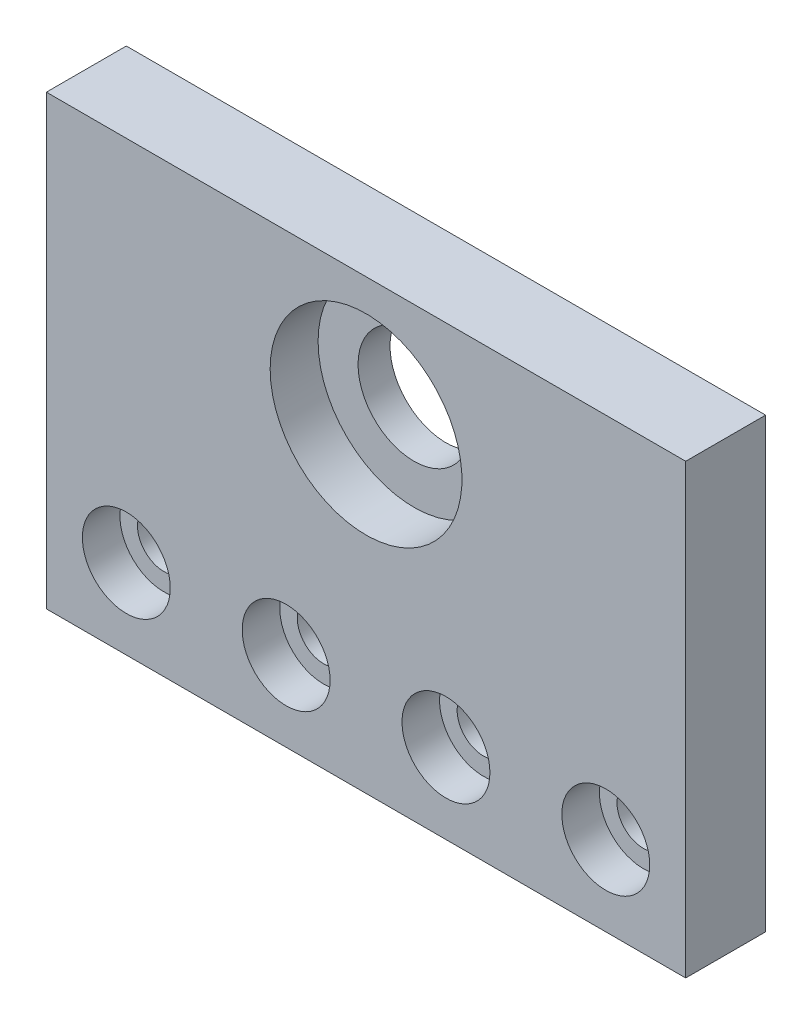
SolidWorks part; units mm, degrees
material "7A04-T6"
ref_plane "前视基准面" through (0, 0, 0) normal (0, 0, 1) x (1, 0, 0)
ref_plane "上视基准面" through (0, 0, 0) normal (0, 1, 0) x (1, 0, 0)
ref_plane "右视基准面" through (0, 0, 0) normal (1, 0, 0) x (0, 0, -1)
sketch "草图1" plane through (0, 0, 0) normal (0, 0, 1) x (1, 0, 0)
  line L1 (-40, -40) -> (40, -40)
  line L2 (-40, -40) -> (-40, 16)
  line L3 (-40, 16) -> (40, 16)
  line L4 (40, -40) -> (40, 16)
  point P4 (0, 16)
  dimension "D1" = 40
  dimension "D2" = 80
  dimension "D3" = 56
extrude "凸台-拉伸1" add sketch "草图1" against normal blind 10
sketch "草图2" plane through (0, 0, 0) normal (0, 0, 1) x (1, 0, 0)
  circle A0 centre (0, 0) radius 19
  dimension "D1" = 38
sketch "草图3" plane through (0, 0, 0) normal (0, 0, 1) x (1, 0, 0)
  line L0 (-40, -40) -> (40, -40) construction
  line L1 (40, -40) -> (40, 16) construction
  line L2 (0, 0) -> (0, -16.4447) construction
  point P0 (30, -30)
  point P9 (-30, -30)
  point P16 (10, -30)
  point P17 (-10, -30)
  point P18 (-30, -30)
  dimension "D1" = 10
  dimension "D2" = 10
  dimension "D3" = 4
hole_wizard "M6 内六角花型圆柱头螺钉的柱形沉头孔1" positions "草图3" profile "草图4" counterbore size "M6" standard "GB" end condition through all
sketch "草图4" plane through (30, -30, 0) normal (1, 0, 0) x (0, -1, 0)
  line L0 (0, 0) -> (0, 10)
  line L1 (0, 10) -> (3.3, 10)
  line L3 (3.3, 10) -> (3.3, 4.7)
  line L4 (3.3, 4.7) -> (5.5, 4.7)
  line L5 (5.5, 4.7) -> (5.5, 0)
  line L7 (5.5, 0) -> (0, 0)
  line L11 (0, -6.35) -> (0, 107.95) construction
  dimension "通孔孔直径" = 6.6
  dimension "通孔孔深度" = 10
  dimension "柱形沉头孔直径" = 11
  dimension "柱形沉头孔深度" = 4.7
sketch "草图5" plane through (0, 0, 0) normal (0, 0, 1) x (1, 0, 0)
  circle A0 centre (0, 0) radius 7
  dimension "D1" = 14
extrude "切除-拉伸1" cut sketch "草图5" against normal blind 10
sketch "草图6" plane through (0, 0, 0) normal (0, 0, -1) x (-1, 0, 0)
  circle A0 centre (0, 0) radius 12
  dimension "D1" = 24
extrude "切除-拉伸2" cut sketch "草图6" along normal blind 6
sketch "草图7" plane through (0, 0, -10) normal (0, 0, -1) x (-1, 0, 0)
  line L0 (40, 16) -> (40, -40) construction
  circle A0 centre (30, 0) radius 5
  dimension "D1" = 10
  dimension "D2" = 10
extrude "切除-拉伸3" cut sketch "草图7" against normal blind 5
mirror "镜向1" about plane through (0, 0, 0) normal (1, 0, 0) of "切除-拉伸3"
